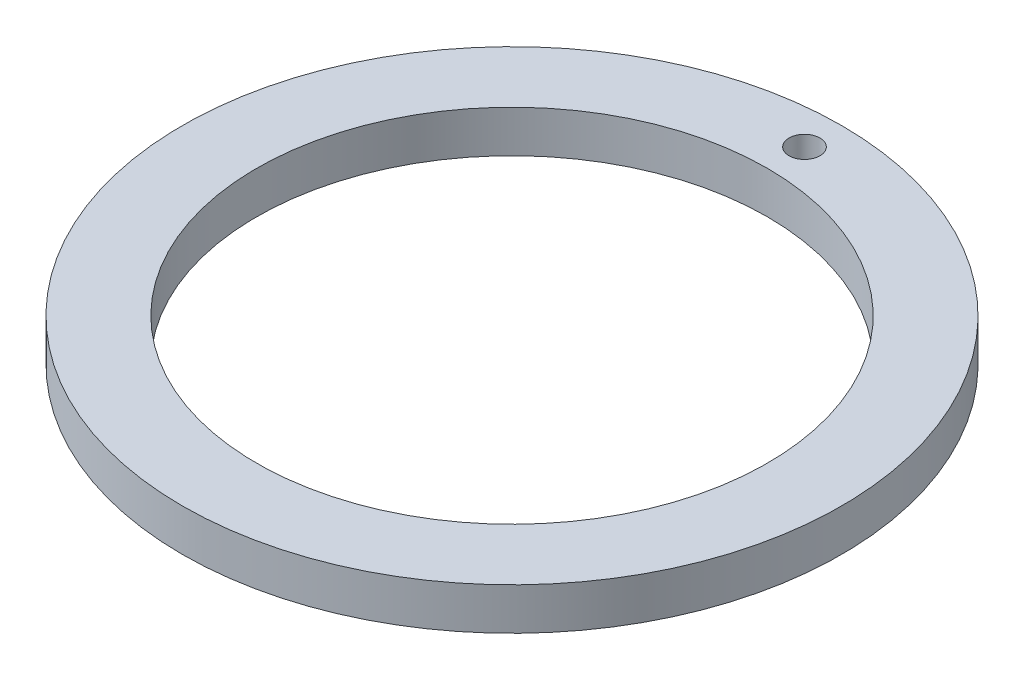
SolidWorks part; units mm, degrees
ref_plane "Front Plane" through (0, 0, 0) normal (0, 0, 1) x (1, 0, 0)
ref_plane "Top Plane" through (0, 0, 0) normal (0, 1, 0) x (1, 0, 0)
ref_plane "Right Plane" through (0, 0, 0) normal (1, 0, 0) x (0, 0, -1)
sketch "Sketch1" plane through (0, 0, 0) normal (0, 1, 0) x (1, 0, 0)
  circle A0 centre (0, 0) radius 50.8
  circle A1 centre (0, 0) radius 39.37
  dimension "D1" = 101.6
  dimension "D2" = 78.74
extrude "Boss-Extrude1" add sketch "Sketch1" along normal blind 6.477 contours A0
sketch "Sketch3" plane through (0, 0, 0) normal (0, -1, 0) x (-1, 0, 0)
  circle A0 centre (0, 0) radius 39.37
  dimension "D1" = 78.74
extrude "Cut-Extrude1" cut sketch "Sketch3" against normal blind 6.477
sketch "Sketch4" plane through (0, 0, 0) normal (0, -1, 0) x (1, 0, 0)
  line L0 (0, -39.37) -> (0, -50.8) construction
  circle A0 centre (0, 0) radius 39.37 construction
  circle A1 centre (0, 0) radius 50.8 construction
  circle A2 centre (0, -45.085) radius 2.3812
  dimension "D1" = 4.7625
extrude "Cut-Extrude2" cut sketch "Sketch4" against normal blind 6.477
